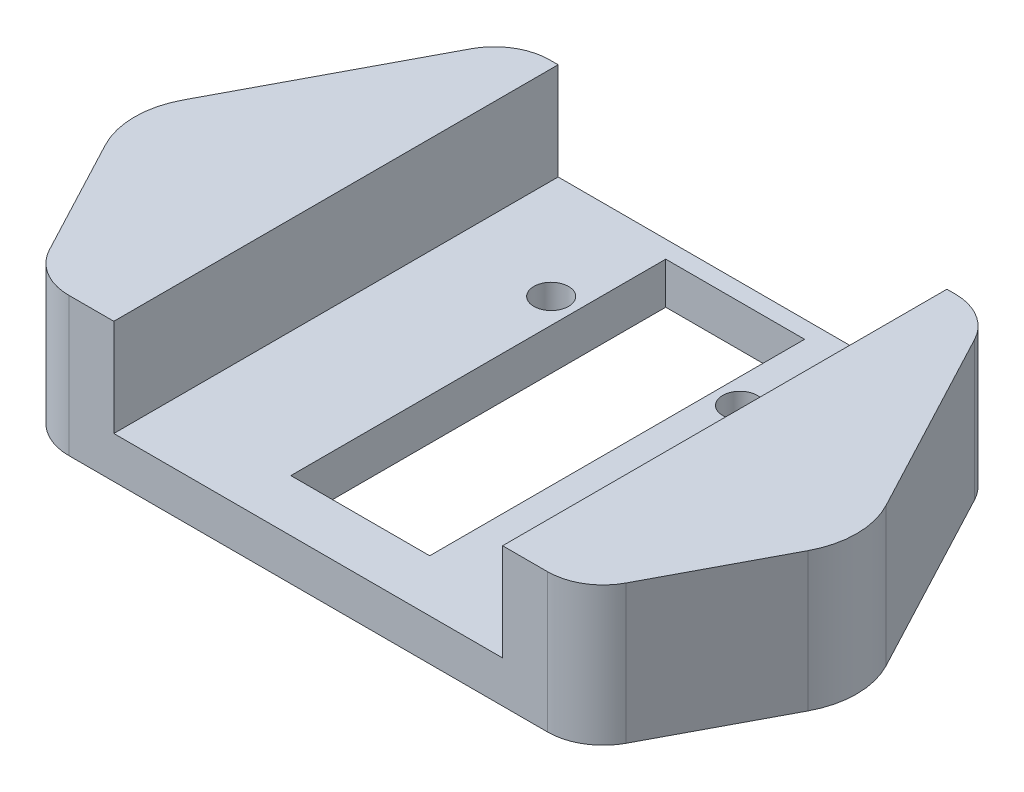
SolidWorks part; units mm, degrees
ref_plane "Front Plane" through (0, 0, 0) normal (0, 0, 1) x (1, 0, 0)
ref_plane "Top Plane" through (0, 0, 0) normal (0, 1, 0) x (1, 0, 0)
ref_plane "Right Plane" through (0, 0, 0) normal (1, 0, 0) x (0, 0, -1)
sketch "Sketch1" plane through (0, 0, 0) normal (0, 1, 0) x (1, 0, 0)
  line L9 (-14, -6.25) -> (-14, 13.75)
  line L11 (-10.5, 17.25) -> (10.5, 17.25) construction
  line L13 (14, 13.75) -> (14, -6.25)
  line L15 (-10.5, -9.75) -> (10.5, -9.75) construction
  line L17 (-14, 13.75) -> (-14, 22.25)
  line L18 (-14, 22.25) -> (14, 22.25)
  line L19 (14, 22.25) -> (14, 13.75)
  line L21 (14, -6.25) -> (14, -14.75)
  line L22 (14, -14.75) -> (-14, -14.75)
  line L23 (-14, -14.75) -> (-14, -6.25)
  arc A9 (-14, -6.25) -> (-10.5, -9.75) centre (-10.5, -6.25) ccw construction
  arc A10 (10.5, -9.75) -> (14, -6.25) centre (10.5, -6.25) ccw construction
  arc A11 (-14, 13.75) -> (-10.5, 17.25) centre (-10.5, 13.75) cw construction
  arc A12 (10.5, 17.25) -> (14, 13.75) centre (10.5, 13.75) cw construction
  dimension "D4" = 7
  dimension "D5" = 20
  dimension "D6" = 5
extrude "Boss-Extrude3" add sketch "Sketch1" along normal blind 3
sketch "Sketch14" plane through (0, 0, 0) normal (0, -1, 0) x (1, 0, 0)
  line L0 (-14, 14.75) -> (14, 14.75) construction
  line L1 (-14, 14.75) -> (-17, 14.75)
  line L2 (-14, 14.75) -> (-14, -22.25)
  line L3 (-14, -22.25) -> (-17, -22.25)
  line L4 (-17, 14.75) -> (-17, -22.25)
  line L5 (14, -22.25) -> (17, -22.25)
  line L6 (14, -22.25) -> (14, 14.75)
  line L7 (14, 14.75) -> (17, 14.75)
  line L8 (17, -22.25) -> (17, 14.75)
  line L9 (14, -22.25) -> (-14, -22.25) construction
  line L10 (-14, -22.25) -> (-14, 14.75) construction
  dimension "D1" = 3
extrude "Boss-Extrude8" add sketch "Sketch14" against normal blind 3
sketch "Sketch15" plane through (0, 0, 0) normal (0, 1, 0) x (1, 0, 0)
  line L0 (-25.3034, 6.556) -> (-17, 22.25)
  line L1 (-25.3034, 0.944) -> (-17, -14.75)
  line L2 (-17, -14.75) -> (-14, -14.75)
  line L3 (-14, -14.75) -> (-14, 22.25)
  line L4 (-14, 22.25) -> (-17, 22.25)
  line L5 (-20, 3.75) -> (-17, 3.75) construction
  line L6 (-17, -14.75) -> (-17, 22.25) construction
  line L7 (17, 22.25) -> (25.3034, 6.556)
  line L8 (25.3034, 0.944) -> (17, -14.75)
  line L9 (17, -14.75) -> (14, -14.75)
  line L10 (14, -14.75) -> (14, 22.25)
  line L11 (14, 22.25) -> (17, 22.25)
  arc A0 (-25.3034, 6.556) -> (-25.3034, 0.944) centre (-20, 3.75) ccw
  circle A1 centre (-20, 3.75) radius 2
  circle A2 centre (20, 3.75) radius 2
  arc A3 (25.3034, 0.944) -> (25.3034, 6.556) centre (20, 3.75) ccw
  dimension "D1" = 4
  dimension "D2" = 12
  dimension "D3" = 6
  dimension "D4" = 3
extrude "Boss-Extrude9" add sketch "Sketch15" along normal blind 10
sketch "Sketch16" plane through (0, 10, 0) normal (0, 1, 0) x (1, 0, 0)
  circle A0 centre (20, 3.75) radius 2 construction
  circle A1 centre (-20, 3.75) radius 2 construction
  circle A2 centre (20, 3.75) radius 2
  circle A3 centre (-20, 3.75) radius 2
extrude "Boss-Extrude10" add sketch "Sketch16" against normal blind 3
sketch "Sketch18" plane through (0, 0, 0) normal (0, -1, 0) x (1, 0, 0)
  line L1 (17, 14.75) -> (25.3034, -0.944) construction
  line L2 (19.6454, 9.75) -> (-19.6454, 9.75)
  line L3 (19.6454, 9.75) -> (19.6454, 14.75)
  line L4 (19.6454, 14.75) -> (-19.6454, 14.75)
  line L5 (-19.6454, 9.75) -> (-19.6454, 14.75)
  line L6 (-25.3034, -0.944) -> (-17, 14.75) construction
  line L7 (-17, 14.75) -> (17, 14.75) construction
  dimension "D1" = 5
extrude "Cut-Extrude6" cut sketch "Sketch18" against normal through all both
fillet "Fillet1" radius 4 4 edges at (19.6454, 5, 9.75) (-19.6454, 5, 9.75) (17, 5, -22.25) (-17, 5, -22.25)
sketch "Sketch19" plane through (0, 3, 0) normal (0, 1, 0) x (1, 0, 0)
  line L0 (0, 17.25) -> (0, -4.75) construction
  line L1 (8.5, 17.25) -> (-8.5, 17.25) construction
  line L2 (-6.65, -4.75) -> (6.65, -4.75) construction
  line L4 (-5, 21) -> (5, 21)
  line L5 (-5, 21) -> (-5, -6)
  line L6 (-5, -6) -> (5, -6)
  line L7 (5, 21) -> (5, -6)
  circle A0 centre (-6.8, 14.55) radius 1.25
  circle A1 centre (6.8, 14.55) radius 1.25
  dimension "D1" = 5
  dimension "D2" = 10
  dimension "D3" = 27
  dimension "D4" = 6
extrude "Cut-Extrude7" cut sketch "Sketch19" against normal blind 10
